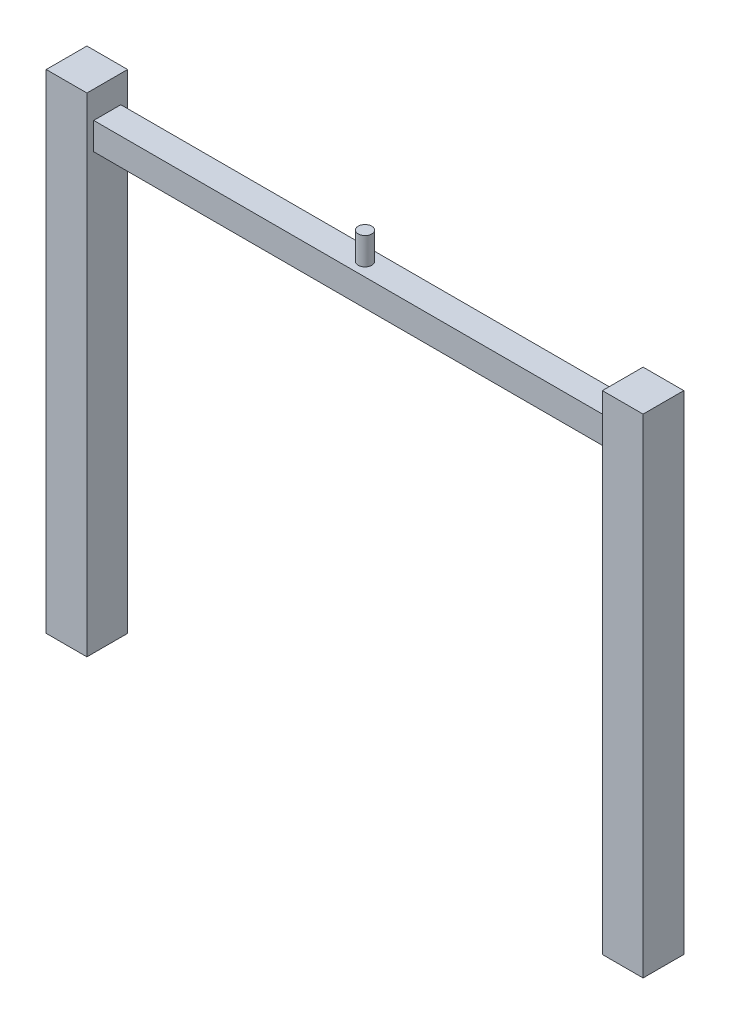
SolidWorks part; units mm, degrees
ref_plane "Front Plane" through (0, 0, 0) normal (0, 0, 1) x (1, 0, 0)
ref_plane "Top Plane" through (0, 0, 0) normal (0, 1, 0) x (1, 0, 0)
ref_plane "Right Plane" through (0, 0, 0) normal (1, 0, 0) x (0, 0, -1)
sketch "Sketch1" plane through (0, 0, 0) normal (0, 1, 0) x (1, 0, 0)
  line L0 (-260.35, 0) -> (260.35, 0) construction
  line L1 (-279.4, 19.05) -> (-241.3, 19.05)
  line L2 (-279.4, 19.05) -> (-279.4, -19.05)
  line L3 (-279.4, -19.05) -> (-241.3, -19.05)
  line L4 (-241.3, 19.05) -> (-241.3, -19.05)
  line L5 (-279.4, 19.05) -> (-241.3, -19.05) construction
  line L6 (-279.4, -19.05) -> (-241.3, 19.05) construction
  line L7 (241.3, 19.05) -> (279.4, 19.05)
  line L8 (241.3, 19.05) -> (241.3, -19.05)
  line L9 (241.3, -19.05) -> (279.4, -19.05)
  line L10 (279.4, 19.05) -> (279.4, -19.05)
  line L11 (241.3, 19.05) -> (279.4, -19.05) construction
  line L12 (241.3, -19.05) -> (279.4, 19.05) construction
  point P0 (-260.35, 0)
  point P5 (260.35, 0)
  point P10 (-279.4, 0)
  point P11 (0, 0)
  dimension "D1" = 38.1
  dimension "D2" = 38.1
  dimension "D3" = 558.8
extrude "Boss-Extrude1" add sketch "Sketch1" along normal blind 457.2
sketch "Sketch2" plane through (279.4, 0, 0) normal (1, 0, 0) x (0, 0, -1)
  line L0 (-19.05, 457.2) -> (19.05, 457.2) construction
  line L1 (-12.7, 431.8) -> (12.7, 431.8)
  line L2 (-12.7, 431.8) -> (-12.7, 406.4)
  line L3 (-12.7, 406.4) -> (12.7, 406.4)
  line L4 (12.7, 431.8) -> (12.7, 406.4)
  line L5 (-12.7, 431.8) -> (12.7, 406.4) construction
  line L6 (-12.7, 406.4) -> (12.7, 431.8) construction
  point P0 (0, 419.1)
  point P7 (0, 457.2)
  dimension "D1" = 25.4
  dimension "D2" = 25.4
extrude "Boss-Extrude2" add sketch "Sketch2" against normal blind 521.97
sketch "Sketch3" plane through (0, 0, 0) normal (0, 1, 0) x (1, 0, 0)
  line L0 (-241.3, 0) -> (241.3, 0) construction
  line L1 (-241.3, -12.7) -> (-241.3, 12.7) construction
  line L2 (241.3, -12.7) -> (241.3, 12.7) construction
  circle A0 centre (0, 0) radius 6.35
  dimension "D1" = 12.7
extrude "Boss-Extrude3" add sketch "Sketch3" along normal blind 25.4 from offset 431.8
